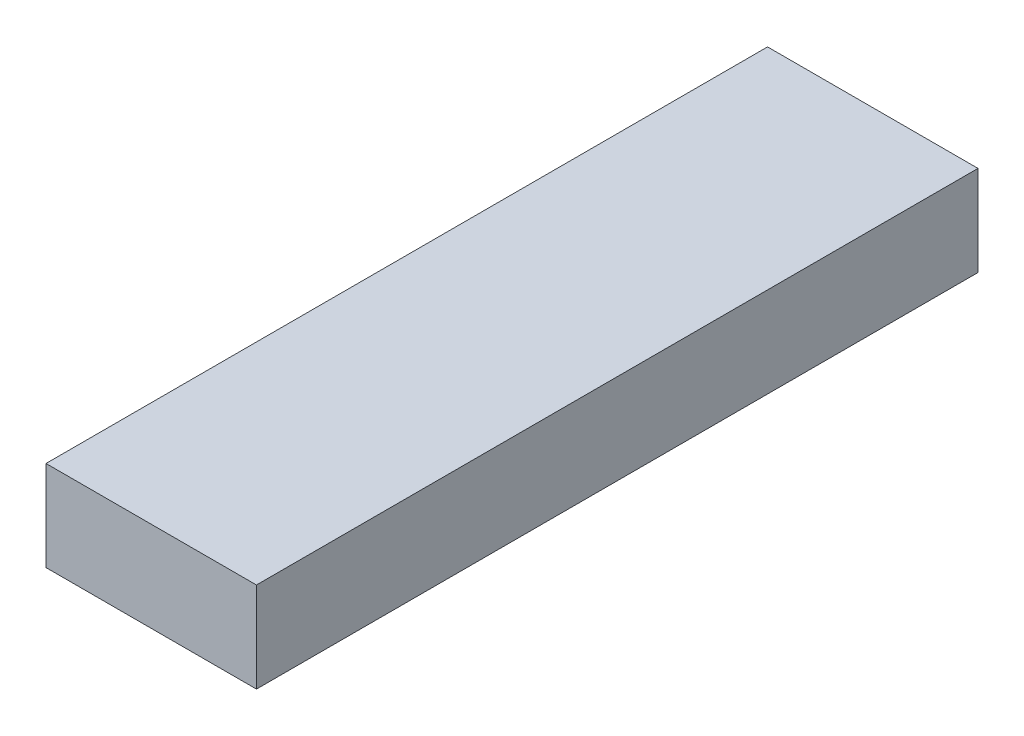
SolidWorks part; units mm, degrees
material "Oak"
ref_plane "Front Plane" through (0, 0, 0) normal (0, 0, 1) x (1, 0, 0)
ref_plane "Top Plane" through (0, 0, 0) normal (0, 1, 0) x (1, 0, 0)
ref_plane "Right Plane" through (0, 0, 0) normal (1, 0, 0) x (0, 0, -1)
sketch "Sketch1" plane through (0, 0, 0) normal (0, 0, 1) x (1, 0, 0)
  line L1 (-44.45, -19.05) -> (44.45, -19.05)
  line L2 (-44.45, -19.05) -> (-44.45, 19.05)
  line L3 (-44.45, 19.05) -> (44.45, 19.05)
  line L4 (44.45, -19.05) -> (44.45, 19.05)
  line L5 (-44.45, -19.05) -> (44.45, 19.05) construction
  line L6 (-44.45, 19.05) -> (44.45, -19.05) construction
  point P0 (0, 0)
  dimension "D1" = 38.1
  dimension "D2" = 88.9
extrude "Boss-Extrude1" add sketch "Sketch1" along normal mid plane 304.8
